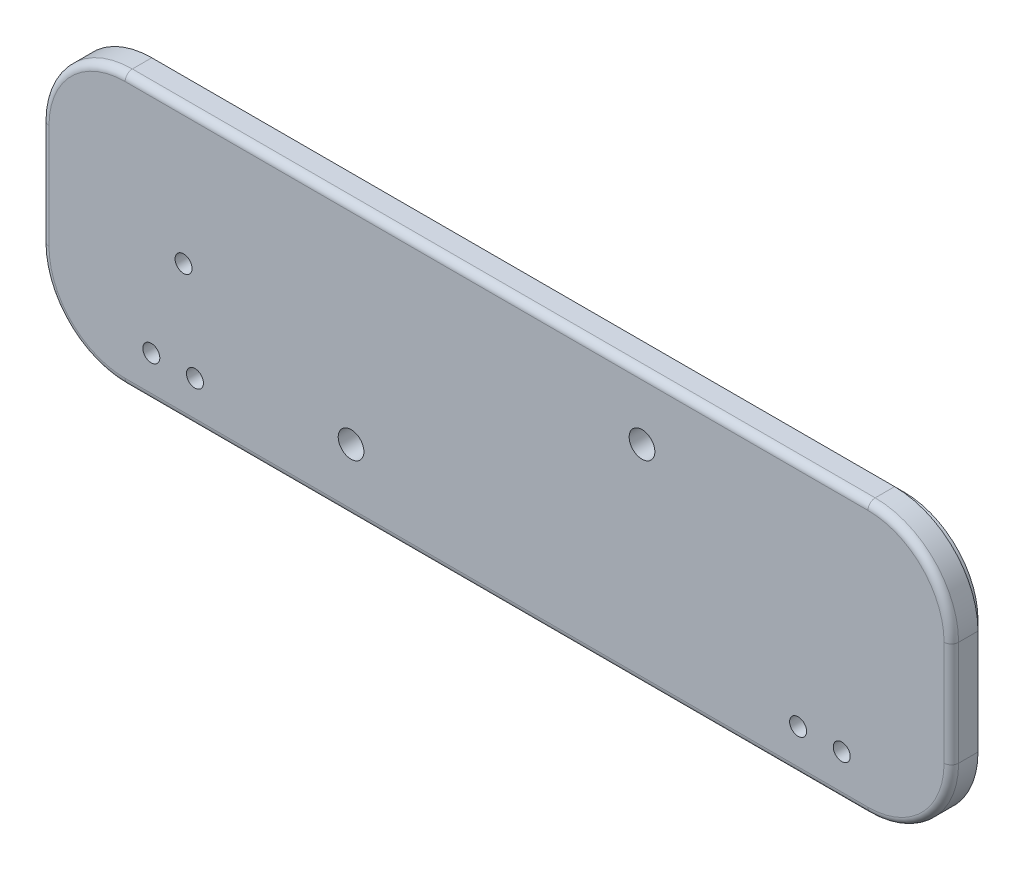
SolidWorks part; units mm, degrees
ref_plane "Front" through (0, 0, 0) normal (0, 0, 1) x (1, 0, 0)
ref_plane "Top" through (0, 0, 0) normal (0, 1, 0) x (1, 0, 0)
ref_plane "Right" through (0, 0, 0) normal (1, 0, 0) x (0, 0, -1)
ref_plane "Plane1" through (0, 0, -1.397) normal (0, 0, -1) x (-1, 0, 0)
sketch "Sketch1" plane through (0, 0, -1.397) normal (0, 0, -1) x (-1, 0, 0)
  line L0 (-23.8252, 7.112) -> (-23.8252, -7.112)
  line L1 (-23.8252, -7.112) -> (23.8252, -7.112)
  line L2 (23.8252, -7.112) -> (23.8252, 7.112)
  line L3 (23.8252, 7.112) -> (-23.8252, 7.112)
  line L4 (-23.8252, -7.112) -> (23.8252, 7.112) construction
  dimension "D1" = 47.6504
  dimension "D2" = 14.224
extrude "Boss-Extrude1" add sketch "Sketch1" against normal blind 1.397
sketch "Sketch2" plane through (0, 0, -1.397) normal (0, 0, -1) x (-1, 0, 0)
  line L0 (23.3172, -6.604) -> (-23.3172, -6.604)
  line L1 (-23.3172, -6.604) -> (-23.3172, 6.604)
  line L2 (-23.3172, 6.604) -> (23.3172, 6.604)
  line L3 (23.3172, 6.604) -> (23.3172, -6.604)
  line L4 (-23.8252, 7.112) -> (-23.8252, -7.112) construction
  line L5 (23.8252, 7.112) -> (-23.8252, 7.112) construction
  dimension "D1" = 0.508
  dimension "D2" = 47.1424
  dimension "D3" = 0.508
  dimension "D4" = 13.716
extrude "Boss-Extrude2" add sketch "Sketch2" along normal blind 0.508
ref_plane "Plane2" through (0, 0, 0) normal (0, -1, 0) x (1, 0, 0)
sketch "Sketch3" plane through (0, 0, 0) normal (0, -1, 0) x (1, 0, 0)
  line L0 (-15.9512, 0) -> (-16.3957, 0)
  line L1 (-16.3957, 0) -> (-16.3957, -1.905)
  line L2 (-16.3957, -1.905) -> (-16.0147, -1.905)
  line L3 (-15.9512, -1.651) -> (-15.9512, 0)
  line L4 (-15.9512, -1.651) -> (-16.0147, -1.651)
  line L5 (-16.0147, -1.905) -> (-16.0147, -1.651)
  line L6 (-16.3957, 0) -> (-16.3957, -1.905) construction
  line L7 (23.8252, 0) -> (-23.8252, 0) construction
  dimension "D1" = 0.381
  dimension "D3" = 1.651
  dimension "D4" = 1.905
revolve "Cut-Revolve1" cut sketch "Sketch3" angle 360 about L6
ref_plane "Plane4" through (0, -4.9022, 0) normal (0, -1, 0) x (1, 0, 0)
sketch "Sketch6" plane through (0, -4.9022, 0) normal (0, -1, 0) x (1, 0, 0)
  line L0 (-15.3543, 0) -> (-15.7988, 0)
  line L1 (-15.7988, 0) -> (-15.7988, -1.905)
  line L2 (-15.7988, -1.905) -> (-15.4178, -1.905)
  line L3 (-15.3543, -1.778) -> (-15.3543, 0)
  line L4 (-15.3543, -1.778) -> (-15.4178, -1.778)
  line L5 (-15.4178, -1.905) -> (-15.4178, -1.778)
  line L6 (-15.7988, 0) -> (-15.7988, -1.905) construction
  line L7 (23.3172, -1.905) -> (-23.3172, -1.905) construction
  line L8 (-15.7988, 0) -> (-15.7988, 1.5963) construction
  line L9 (23.8252, 0) -> (-23.8252, 0) construction
  dimension "D1" = 0.381
  dimension "D2" = 0.4445
  dimension "D3" = 0.127
  dimension "D4" = 1.905
  dimension "D5" = 15.7988
revolve "Cut-Revolve4" cut sketch "Sketch6" angle 360 about L6
fillet "Fillet1" radius 3.8608 1 edges at (23.3172, -6.604, -1.651)
fillet "Fillet2" radius 3.8608 1 edges at (-23.3172, -6.604, -1.651)
fillet "Fillet3" radius 3.8608 1 edges at (-23.3172, 6.604, -1.651)
fillet "Fillet4" radius 3.8608 1 edges at (23.3172, 6.604, -1.651)
fillet "Fillet5" radius 4.3688 1 edges at (-23.8252, -7.112, -0.6985)
fillet "Fillet6" radius 4.3688 1 edges at (-23.8252, 7.112, -0.6985)
fillet "Fillet7" radius 4.3688 1 edges at (23.8252, 7.112, -0.6985)
fillet "Fillet8" radius 4.3688 1 edges at (23.8252, -7.112, -0.6985)
fillet "Fillet9" radius 0.381 8 edges at (22.5456, -5.8324, 0) (23.8252, 0, 0) (0, -7.112, 0) (22.5456, 5.8324, 0) (-22.5456, -5.8324, 0) (0, 7.112, 0) (-23.8252, 0, 0) (-22.5456, 5.8324, 0)
pattern_linear "LPattern1" count 2 spacing 2.286 along (-1, 0, 0) of "Cut-Revolve4"
mirror "Mirror1" about plane through (0, 0, 0) normal (1, 0, 0) of "LPattern1", "Cut-Revolve4"
sketch "Sketch7" plane through (0, 0, 0) normal (0, 0, 1) x (1, 0, 0)
  line L0 (-7.62, -3.81) -> (7.62, 3.81) construction
  circle A0 centre (-7.62, -3.81) radius 0.6731
  circle A1 centre (7.62, 3.81) radius 0.6731
  dimension "D1" = 1.3462
  dimension "D2" = 15.24
  dimension "D3" = 7.62
extrude "Cut-Extrude1" cut sketch "Sketch7" against normal through all
sketch "Sketch8" plane through (0, 0, -1.905) normal (0, 0, -1) x (-1, 0, 0)
  line L0 (-6.8322, -4.9022) -> (6.8322, -4.9022) construction
  circle A0 centre (0, -4.9022) radius 0.1715
  dimension "D1" = 0.3429
extrude "Cut-Extrude2" cut sketch "Sketch8" against normal blind 1.27
